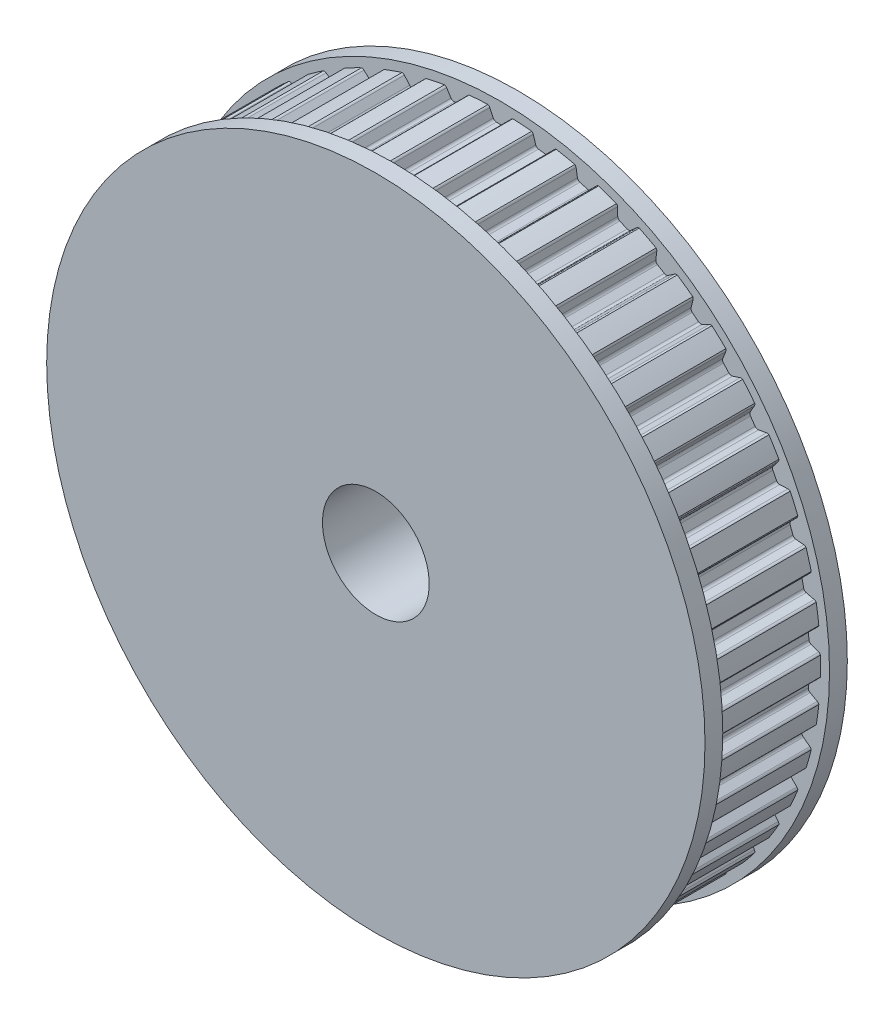
SolidWorks part; units mm, degrees
ref_plane "Front Plane" through (0, 0, 0) normal (0, 0, 1) x (1, 0, 0)
ref_plane "Top Plane" through (0, 0, 0) normal (0, 1, 0) x (1, 0, 0)
ref_plane "Right Plane" through (0, 0, 0) normal (1, 0, 0) x (0, 0, -1)
sketch "Sketch1" plane through (0, 0, 0) normal (1, 0, 0) x (0, 0, -1)
  line L0 (141.7526, 0) -> (-141.7526, 0) construction
  line L1 (0, -176.0309) -> (0, 176.0309) construction
  line L2 (15, 6) -> (-15, 6)
  line L3 (-15, 6) -> (-15, 37)
  line L4 (-15, 37) -> (-13, 37)
  line L5 (-13, 37) -> (-13, 36)
  line L6 (-13, 36) -> (-1, 36)
  line L7 (-1, 36) -> (-1, 37)
  line L8 (-1, 37) -> (1, 37)
  line L9 (15, 6) -> (15, 10)
  line L10 (15, 10) -> (1, 10)
  line L11 (1, 10) -> (1, 37)
  point P4 (0, 0)
  point P8 (0, 0)
  point P11 (0, 6)
  dimension "D1" = 30
  dimension "D2" = 6
  dimension "D3" = 31
  dimension "D4" = 2
  dimension "D5" = 30
  dimension "D6" = 12
  dimension "D7" = 10
revolve "Revolve1" add sketch "Sketch1" angle 360 about L0
sketch "Sketch2" plane through (0, 0, 1) normal (0, 0, 1) x (1, 0, 0)
  line L0 (0, -36) -> (0, 36) construction
  line L1 (0.4522, 34.73) -> (-0.4522, 34.73)
  line L2 (-0.7966, 34.9494) -> (-1.1842, 35.7807)
  line L3 (0.7966, 34.9494) -> (1.1842, 35.7807)
  line L4 (5.5481, 34.5154) -> (6.0453, 35.2861)
  line L5 (5.1771, 34.3449) -> (4.2811, 34.4681)
  line L6 (3.9698, 34.7324) -> (3.6989, 35.6086)
  line L7 (10.1963, 33.4385) -> (10.7938, 34.1343)
  line L8 (9.8055, 33.3201) -> (8.9346, 33.5641)
  line L9 (8.6622, 33.8683) -> (8.5132, 34.7733)
  line L10 (14.6545, 31.7386) -> (15.3412, 32.3466)
  line L11 (14.2512, 31.6746) -> (13.4217, 32.0349)
  line L12 (13.1932, 32.3734) -> (13.1689, 33.2902)
  line L13 (18.8398, 29.4475) -> (19.6029, 29.9564)
  line L14 (18.4315, 29.439) -> (17.6588, 29.9089)
  line L15 (17.4785, 30.2754) -> (17.5792, 31.187)
  line L16 (22.6741, 26.6079) -> (23.4994, 27.0081)
  line L17 (22.2685, 26.6551) -> (21.5669, 27.2258)
  line L18 (21.4382, 27.6134) -> (21.6621, 28.5028)
  line L19 (26.086, 23.2726) -> (26.9581, 23.5567)
  line L20 (25.6906, 23.3746) -> (25.0733, 24.0356)
  line L21 (24.9986, 24.437) -> (25.3415, 25.2877)
  line L22 (29.012, 19.5038) -> (29.9146, 19.6665)
  line L23 (28.6341, 19.6587) -> (28.1126, 20.3975)
  line L24 (28.0932, 20.8054) -> (28.5488, 21.6015)
  line L25 (31.3975, 15.3717) -> (32.3139, 15.41)
  line L26 (31.0443, 15.5766) -> (30.6282, 16.3796)
  line L27 (30.6646, 16.7863) -> (31.2243, 17.5129)
  line L28 (33.1982, 10.9532) -> (34.1113, 10.8664)
  line L29 (32.8762, 11.2043) -> (32.5733, 12.0565)
  line L30 (32.6647, 12.4544) -> (33.3181, 13.0981)
  line L31 (34.3805, 6.3307) -> (35.2732, 6.1203)
  line L32 (34.0956, 6.6233) -> (33.9116, 7.5088)
  line L33 (34.0563, 7.8906) -> (34.7913, 8.4392)
  line L34 (34.9223, 1.5903) -> (35.7781, 1.2603)
  line L35 (34.6799, 1.9189) -> (34.6182, 2.8212)
  line L36 (34.8136, 3.1798) -> (35.6164, 3.6232)
  line L37 (34.8136, -3.1798) -> (35.6164, -3.6232)
  line L38 (34.6182, -2.8212) -> (34.6799, -1.9189)
  line L39 (34.9223, -1.5903) -> (35.7781, -1.2603)
  line L40 (34.0563, -7.8906) -> (34.7913, -8.4392)
  line L41 (33.9116, -7.5088) -> (34.0956, -6.6233)
  line L42 (34.3805, -6.3307) -> (35.2732, -6.1203)
  line L43 (32.6647, -12.4544) -> (33.3181, -13.0981)
  line L44 (32.5733, -12.0565) -> (32.8762, -11.2043)
  line L45 (33.1982, -10.9532) -> (34.1113, -10.8664)
  line L46 (30.6646, -16.7863) -> (31.2243, -17.5129)
  line L47 (30.6282, -16.3796) -> (31.0443, -15.5766)
  line L48 (31.3975, -15.3717) -> (32.3139, -15.41)
  line L49 (28.0932, -20.8054) -> (28.5488, -21.6015)
  line L50 (28.1126, -20.3975) -> (28.6341, -19.6587)
  line L51 (29.012, -19.5038) -> (29.9146, -19.6665)
  line L52 (24.9986, -24.437) -> (25.3415, -25.2877)
  line L53 (25.0733, -24.0356) -> (25.6906, -23.3746)
  line L54 (26.086, -23.2726) -> (26.9581, -23.5567)
  line L55 (21.4382, -27.6134) -> (21.6621, -28.5028)
  line L56 (21.5669, -27.2258) -> (22.2685, -26.6551)
  line L57 (22.6741, -26.6079) -> (23.4994, -27.0081)
  line L58 (17.4785, -30.2754) -> (17.5792, -31.187)
  line L59 (17.6588, -29.9089) -> (18.4315, -29.439)
  line L60 (18.8398, -29.4475) -> (19.6029, -29.9564)
  line L61 (13.1932, -32.3734) -> (13.1689, -33.2902)
  line L62 (13.4217, -32.0349) -> (14.2512, -31.6746)
  line L63 (14.6545, -31.7386) -> (15.3412, -32.3466)
  line L64 (8.6622, -33.8683) -> (8.5132, -34.7733)
  line L65 (8.9346, -33.5641) -> (9.8055, -33.3201)
  line L66 (10.1963, -33.4385) -> (10.7938, -34.1343)
  line L67 (3.9698, -34.7324) -> (3.6989, -35.6086)
  line L68 (4.2811, -34.4681) -> (5.1771, -34.3449)
  line L69 (5.5481, -34.5154) -> (6.0453, -35.2861)
  line L70 (-0.7966, -34.9494) -> (-1.1842, -35.7807)
  line L71 (-0.4522, -34.73) -> (0.4522, -34.73)
  line L72 (0.7966, -34.9494) -> (1.1842, -35.7807)
  line L73 (-5.5481, -34.5154) -> (-6.0453, -35.2861)
  line L74 (-5.1771, -34.3449) -> (-4.2811, -34.4681)
  line L75 (-3.9698, -34.7324) -> (-3.6989, -35.6086)
  line L76 (-10.1963, -33.4385) -> (-10.7938, -34.1343)
  line L77 (-9.8055, -33.3201) -> (-8.9346, -33.5641)
  line L78 (-8.6622, -33.8683) -> (-8.5132, -34.7733)
  line L79 (-14.6545, -31.7386) -> (-15.3412, -32.3466)
  line L80 (-14.2512, -31.6746) -> (-13.4217, -32.0349)
  line L81 (-13.1932, -32.3734) -> (-13.1689, -33.2902)
  line L82 (-18.8398, -29.4475) -> (-19.6029, -29.9564)
  line L83 (-18.4315, -29.439) -> (-17.6588, -29.9089)
  line L84 (-17.4785, -30.2754) -> (-17.5792, -31.187)
  line L85 (-22.6741, -26.6079) -> (-23.4994, -27.0081)
  line L86 (-22.2685, -26.6551) -> (-21.5669, -27.2258)
  line L87 (-21.4382, -27.6134) -> (-21.6621, -28.5028)
  line L88 (-26.086, -23.2726) -> (-26.9581, -23.5567)
  line L89 (-25.6906, -23.3746) -> (-25.0733, -24.0356)
  line L90 (-24.9986, -24.437) -> (-25.3415, -25.2877)
  line L91 (-29.012, -19.5038) -> (-29.9146, -19.6665)
  line L92 (-28.6341, -19.6587) -> (-28.1126, -20.3975)
  line L93 (-28.0932, -20.8054) -> (-28.5488, -21.6015)
  line L94 (-31.3975, -15.3717) -> (-32.3139, -15.41)
  line L95 (-31.0443, -15.5766) -> (-30.6282, -16.3796)
  line L96 (-30.6646, -16.7863) -> (-31.2243, -17.5129)
  line L97 (-33.1982, -10.9532) -> (-34.1113, -10.8664)
  line L98 (-32.8762, -11.2043) -> (-32.5733, -12.0565)
  line L99 (-32.6647, -12.4544) -> (-33.3181, -13.0981)
  line L100 (-34.3805, -6.3307) -> (-35.2732, -6.1203)
  line L101 (-34.0956, -6.6233) -> (-33.9116, -7.5088)
  line L102 (-34.0563, -7.8906) -> (-34.7913, -8.4392)
  line L103 (-34.9223, -1.5903) -> (-35.7781, -1.2603)
  line L104 (-34.6799, -1.9189) -> (-34.6182, -2.8212)
  line L105 (-34.8136, -3.1798) -> (-35.6164, -3.6232)
  line L106 (-34.8136, 3.1798) -> (-35.6164, 3.6232)
  line L107 (-34.6182, 2.8212) -> (-34.6799, 1.9189)
  line L108 (-34.9223, 1.5903) -> (-35.7781, 1.2603)
  line L109 (-34.0563, 7.8906) -> (-34.7913, 8.4392)
  line L110 (-33.9116, 7.5088) -> (-34.0956, 6.6233)
  line L111 (-34.3805, 6.3307) -> (-35.2732, 6.1203)
  line L112 (-32.6647, 12.4544) -> (-33.3181, 13.0981)
  line L113 (-32.5733, 12.0565) -> (-32.8762, 11.2043)
  line L114 (-33.1982, 10.9532) -> (-34.1113, 10.8664)
  line L115 (-30.6646, 16.7863) -> (-31.2243, 17.5129)
  line L116 (-30.6282, 16.3796) -> (-31.0443, 15.5766)
  line L117 (-31.3975, 15.3717) -> (-32.3139, 15.41)
  line L118 (-28.0932, 20.8054) -> (-28.5488, 21.6015)
  line L119 (-28.1126, 20.3975) -> (-28.6341, 19.6587)
  line L120 (-29.012, 19.5038) -> (-29.9146, 19.6665)
  line L121 (-24.9986, 24.437) -> (-25.3415, 25.2877)
  line L122 (-25.0733, 24.0356) -> (-25.6906, 23.3746)
  line L123 (-26.086, 23.2726) -> (-26.9581, 23.5567)
  line L124 (-21.4382, 27.6134) -> (-21.6621, 28.5028)
  line L125 (-21.5669, 27.2258) -> (-22.2685, 26.6551)
  line L126 (-22.6741, 26.6079) -> (-23.4994, 27.0081)
  line L127 (-17.4785, 30.2754) -> (-17.5792, 31.187)
  line L128 (-17.6588, 29.9089) -> (-18.4315, 29.439)
  line L129 (-18.8398, 29.4475) -> (-19.6029, 29.9564)
  line L130 (-13.1932, 32.3734) -> (-13.1689, 33.2902)
  line L131 (-13.4217, 32.0349) -> (-14.2512, 31.6746)
  line L132 (-14.6545, 31.7386) -> (-15.3412, 32.3466)
  line L133 (-8.6622, 33.8683) -> (-8.5132, 34.7733)
  line L134 (-8.9346, 33.5641) -> (-9.8055, 33.3201)
  line L135 (-10.1963, 33.4385) -> (-10.7938, 34.1343)
  line L136 (-3.9698, 34.7324) -> (-3.6989, 35.6086)
  line L137 (-4.2811, 34.4681) -> (-5.1771, 34.3449)
  line L138 (-5.5481, 34.5154) -> (-6.0453, 35.2861)
  line L139 (1.5217, 36) -> (3.3945, 35.8719)
  line L140 (6.4095, 35.4575) -> (8.2474, 35.0756)
  line L141 (11.1779, 34.2545) -> (12.9467, 33.6258)
  line L142 (15.7381, 32.4134) -> (17.4049, 31.5497)
  line L143 (20.0052, 29.9685) -> (21.5388, 28.8859)
  line L144 (23.8995, 26.9653) -> (25.2715, 25.684)
  line L145 (27.3487, 23.4598) -> (28.5334, 22.0037)
  line L146 (30.2884, 19.5173) -> (31.2638, 17.9134)
  line L147 (32.6639, 15.2113) -> (33.4118, 13.4895)
  line L148 (34.431, 10.6219) -> (34.9374, 8.8143)
  line L149 (35.5566, 5.8346) -> (35.8122, 3.9748)
  line L150 (36.0199, 0.9386) -> (36.0199, -0.9386)
  line L151 (35.8122, -3.9748) -> (35.5566, -5.8346)
  line L152 (34.9374, -8.8143) -> (34.431, -10.6219)
  line L153 (33.4118, -13.4895) -> (32.6639, -15.2113)
  line L154 (31.2638, -17.9134) -> (30.2884, -19.5173)
  line L155 (28.5334, -22.0037) -> (27.3487, -23.4598)
  line L156 (25.2715, -25.684) -> (23.8995, -26.9653)
  line L157 (21.5388, -28.8859) -> (20.0052, -29.9685)
  line L158 (17.4049, -31.5497) -> (15.7381, -32.4134)
  line L159 (12.9467, -33.6258) -> (11.1779, -34.2545)
  line L160 (8.2474, -35.0756) -> (6.4095, -35.4575)
  line L161 (3.3945, -35.8719) -> (1.5217, -36)
  line L162 (-1.5217, -36) -> (-3.3945, -35.8719)
  line L163 (-6.4095, -35.4575) -> (-8.2474, -35.0756)
  line L164 (-11.1779, -34.2545) -> (-12.9467, -33.6258)
  line L165 (-15.7381, -32.4134) -> (-17.4049, -31.5497)
  line L166 (-20.0052, -29.9685) -> (-21.5388, -28.8859)
  line L167 (-23.8995, -26.9653) -> (-25.2715, -25.684)
  line L168 (-27.3487, -23.4598) -> (-28.5334, -22.0037)
  line L169 (-30.2884, -19.5173) -> (-31.2638, -17.9134)
  line L170 (-32.6639, -15.2113) -> (-33.4118, -13.4895)
  line L171 (-34.431, -10.6219) -> (-34.9374, -8.8143)
  line L172 (-35.5566, -5.8346) -> (-35.8122, -3.9748)
  line L173 (-36.0199, -0.9386) -> (-36.0199, 0.9386)
  line L174 (-35.8122, 3.9748) -> (-35.5566, 5.8346)
  line L175 (-34.9374, 8.8143) -> (-34.431, 10.6219)
  line L176 (-33.4118, 13.4895) -> (-32.6639, 15.2113)
  line L177 (-31.2638, 17.9134) -> (-30.2884, 19.5173)
  line L178 (-28.5334, 22.0037) -> (-27.3487, 23.4598)
  line L179 (-25.2715, 25.684) -> (-23.8995, 26.9653)
  line L180 (-21.5388, 28.8859) -> (-20.0052, 29.9685)
  line L181 (-17.4049, 31.5497) -> (-15.7381, 32.4134)
  line L182 (-12.9467, 33.6258) -> (-11.1779, 34.2545)
  line L183 (-8.2474, 35.0756) -> (-6.4095, 35.4575)
  line L184 (-3.3945, 35.8719) -> (-1.5217, 36)
  circle A0 centre (0, 0) radius 34.73 construction
  circle A1 centre (0, 0) radius 36 construction
  arc A2 (1.1842, 35.7807) -> (1.5217, 36) centre (1.5286, 35.6201) cw
  arc A3 (0.4522, 34.73) -> (0.7966, 34.9494) centre (0.4522, 35.11) ccw
  arc A4 (-0.4522, 34.73) -> (-0.7966, 34.9494) centre (-0.4522, 35.11) cw
  arc A5 (-1.1842, 35.7807) -> (-1.5217, 36) centre (-1.5286, 35.6201) ccw
  arc A6 (6.0453, 35.2861) -> (6.4095, 35.4575) centre (6.3646, 35.0801) cw
  arc A7 (5.1771, 34.3449) -> (5.5481, 34.5154) centre (5.2288, 34.7214) ccw
  arc A8 (4.2811, 34.4681) -> (3.9698, 34.7324) centre (4.3328, 34.8446) cw
  arc A9 (3.6989, 35.6086) -> (3.3945, 35.8719) centre (3.3359, 35.4964) ccw
  arc A10 (10.7938, 34.1343) -> (11.1779, 34.2545) centre (11.0821, 33.8868) cw
  arc A11 (9.8055, 33.3201) -> (10.1963, 33.4385) centre (9.908, 33.686) ccw
  arc A12 (8.9346, 33.5641) -> (8.6622, 33.8683) centre (9.0371, 33.93) cw
  arc A13 (8.5132, 34.7733) -> (8.2474, 35.0756) centre (8.1382, 34.7116) ccw
  arc A14 (15.3412, 32.3466) -> (15.7381, 32.4134) centre (15.5931, 32.0621) cw
  arc A15 (14.2512, 31.6746) -> (14.6545, 31.7386) centre (14.4026, 32.0231) ccw
  arc A16 (13.4217, 32.0349) -> (13.1932, 32.3734) centre (13.5731, 32.3834) cw
  arc A17 (13.1689, 33.2902) -> (12.9467, 33.6258) centre (12.789, 33.2801) ccw
  arc A18 (19.6029, 29.9564) -> (20.0052, 29.9685) centre (19.8137, 29.6402) cw
  arc A19 (18.4315, 29.439) -> (18.8398, 29.4475) centre (18.629, 29.7637) ccw
  arc A20 (17.6588, 29.9089) -> (17.4785, 30.2754) centre (17.8562, 30.2336) cw
  arc A21 (17.5792, 31.187) -> (17.4049, 31.5497) centre (17.2015, 31.2287) ccw
  arc A22 (23.4994, 27.0081) -> (23.8995, 26.9653) centre (23.6652, 26.6662) cw
  arc A23 (22.2685, 26.6551) -> (22.6741, 26.6079) centre (22.5083, 26.9498) ccw
  arc A24 (21.5669, 27.2258) -> (21.4382, 27.6134) centre (21.8067, 27.5206) cw
  arc A25 (21.6621, 28.5028) -> (21.5388, 28.8859) centre (21.2936, 28.5956) ccw
  arc A26 (26.9581, 23.5567) -> (27.3487, 23.4598) centre (27.0758, 23.1954) cw
  arc A27 (25.6906, 23.3746) -> (26.086, 23.2726) centre (25.9683, 23.634) ccw
  arc A28 (25.0733, 24.0356) -> (24.9986, 24.437) centre (25.351, 24.2949) cw
  arc A29 (25.3415, 25.2877) -> (25.2715, 25.684) centre (24.9891, 25.4298) ccw
  arc A30 (29.9146, 19.6665) -> (30.2884, 19.5173) centre (29.982, 19.2926) cw
  arc A31 (28.6341, 19.6587) -> (29.012, 19.5038) centre (28.9446, 19.8778) ccw
  arc A32 (28.1126, 20.3975) -> (28.0932, 20.8054) centre (28.423, 20.6167) cw
  arc A33 (28.5488, 21.6015) -> (28.5334, 22.0037) centre (28.219, 21.7902) ccw
  arc A34 (32.3139, 15.41) -> (32.6639, 15.2113) centre (32.3298, 15.0303) cw
  arc A35 (31.0443, 15.5766) -> (31.3975, 15.3717) centre (31.3817, 15.7514) ccw
  arc A36 (30.6282, 16.3796) -> (30.6646, 16.7863) centre (30.9656, 16.5544) cw
  arc A37 (31.2243, 17.5129) -> (31.2638, 17.9134) centre (30.9233, 17.7448) ccw
  arc A38 (34.1113, 10.8664) -> (34.431, 10.6219) centre (34.0753, 10.4881) cw
  arc A39 (32.8762, 11.2043) -> (33.1982, 10.9532) centre (33.2342, 11.3315) ccw
  arc A40 (32.5733, 12.0565) -> (32.6647, 12.4544) centre (32.9313, 12.1837) cw
  arc A41 (33.3181, 13.0981) -> (33.4118, 13.4895) centre (33.0515, 13.3688) ccw
  arc A42 (35.2732, 6.1203) -> (35.5566, 5.8346) centre (35.186, 5.7505) cw
  arc A43 (34.0956, 6.6233) -> (34.3805, 6.3307) centre (34.4676, 6.7006) ccw
  arc A44 (33.9116, 7.5088) -> (34.0563, 7.8906) centre (34.2836, 7.5861) cw
  arc A45 (34.7913, 8.4392) -> (34.9374, 8.8143) centre (34.564, 8.7438) ccw
  arc A46 (35.7781, 1.2603) -> (36.0199, 0.9386) centre (35.6413, 0.9057) cw
  arc A47 (34.6799, 1.9189) -> (34.9223, 1.5903) centre (35.059, 1.9448) ccw
  arc A48 (34.6182, 2.8212) -> (34.8136, 3.1798) centre (34.9973, 2.8471) cw
  arc A49 (35.6164, 3.6232) -> (35.8122, 3.9748) centre (35.4327, 3.9559) ccw
  arc A50 (35.6164, -3.6232) -> (35.8122, -3.9748) centre (35.4327, -3.9559) cw
  arc A51 (34.6182, -2.8212) -> (34.8136, -3.1798) centre (34.9973, -2.8471) ccw
  arc A52 (34.6799, -1.9189) -> (34.9223, -1.5903) centre (35.059, -1.9448) cw
  arc A53 (35.7781, -1.2603) -> (36.0199, -0.9386) centre (35.6413, -0.9057) ccw
  arc A54 (34.7913, -8.4392) -> (34.9374, -8.8143) centre (34.564, -8.7438) cw
  arc A55 (33.9116, -7.5088) -> (34.0563, -7.8906) centre (34.2836, -7.5861) ccw
  arc A56 (34.0956, -6.6233) -> (34.3805, -6.3307) centre (34.4676, -6.7006) cw
  arc A57 (35.2732, -6.1203) -> (35.5566, -5.8346) centre (35.186, -5.7505) ccw
  arc A58 (33.3181, -13.0981) -> (33.4118, -13.4895) centre (33.0515, -13.3688) cw
  arc A59 (32.5733, -12.0565) -> (32.6647, -12.4544) centre (32.9313, -12.1837) ccw
  arc A60 (32.8762, -11.2043) -> (33.1982, -10.9532) centre (33.2342, -11.3315) cw
  arc A61 (34.1113, -10.8664) -> (34.431, -10.6219) centre (34.0753, -10.4881) ccw
  arc A62 (31.2243, -17.5129) -> (31.2638, -17.9134) centre (30.9233, -17.7448) cw
  arc A63 (30.6282, -16.3796) -> (30.6646, -16.7863) centre (30.9656, -16.5544) ccw
  arc A64 (31.0443, -15.5766) -> (31.3975, -15.3717) centre (31.3817, -15.7514) cw
  arc A65 (32.3139, -15.41) -> (32.6639, -15.2113) centre (32.3298, -15.0303) ccw
  arc A66 (28.5488, -21.6015) -> (28.5334, -22.0037) centre (28.219, -21.7902) cw
  arc A67 (28.1126, -20.3975) -> (28.0932, -20.8054) centre (28.423, -20.6167) ccw
  arc A68 (28.6341, -19.6587) -> (29.012, -19.5038) centre (28.9446, -19.8778) cw
  arc A69 (29.9146, -19.6665) -> (30.2884, -19.5173) centre (29.982, -19.2926) ccw
  arc A70 (25.3415, -25.2877) -> (25.2715, -25.684) centre (24.9891, -25.4298) cw
  arc A71 (25.0733, -24.0356) -> (24.9986, -24.437) centre (25.351, -24.2949) ccw
  arc A72 (25.6906, -23.3746) -> (26.086, -23.2726) centre (25.9683, -23.634) cw
  arc A73 (26.9581, -23.5567) -> (27.3487, -23.4598) centre (27.0758, -23.1954) ccw
  arc A74 (21.6621, -28.5028) -> (21.5388, -28.8859) centre (21.2936, -28.5956) cw
  arc A75 (21.5669, -27.2258) -> (21.4382, -27.6134) centre (21.8067, -27.5206) ccw
  arc A76 (22.2685, -26.6551) -> (22.6741, -26.6079) centre (22.5083, -26.9498) cw
  arc A77 (23.4994, -27.0081) -> (23.8995, -26.9653) centre (23.6652, -26.6662) ccw
  arc A78 (17.5792, -31.187) -> (17.4049, -31.5497) centre (17.2015, -31.2287) cw
  arc A79 (17.6588, -29.9089) -> (17.4785, -30.2754) centre (17.8562, -30.2336) ccw
  arc A80 (18.4315, -29.439) -> (18.8398, -29.4475) centre (18.629, -29.7637) cw
  arc A81 (19.6029, -29.9564) -> (20.0052, -29.9685) centre (19.8137, -29.6402) ccw
  arc A82 (13.1689, -33.2902) -> (12.9467, -33.6258) centre (12.789, -33.2801) cw
  arc A83 (13.4217, -32.0349) -> (13.1932, -32.3734) centre (13.5731, -32.3834) ccw
  arc A84 (14.2512, -31.6746) -> (14.6545, -31.7386) centre (14.4026, -32.0231) cw
  arc A85 (15.3412, -32.3466) -> (15.7381, -32.4134) centre (15.5931, -32.0621) ccw
  arc A86 (8.5132, -34.7733) -> (8.2474, -35.0756) centre (8.1382, -34.7116) cw
  arc A87 (8.9346, -33.5641) -> (8.6622, -33.8683) centre (9.0371, -33.93) ccw
  arc A88 (9.8055, -33.3201) -> (10.1963, -33.4385) centre (9.908, -33.686) cw
  arc A89 (10.7938, -34.1343) -> (11.1779, -34.2545) centre (11.0821, -33.8868) ccw
  arc A90 (3.6989, -35.6086) -> (3.3945, -35.8719) centre (3.3359, -35.4964) cw
  arc A91 (4.2811, -34.4681) -> (3.9698, -34.7324) centre (4.3328, -34.8446) ccw
  arc A92 (5.1771, -34.3449) -> (5.5481, -34.5154) centre (5.2288, -34.7214) cw
  arc A93 (6.0453, -35.2861) -> (6.4095, -35.4575) centre (6.3646, -35.0801) ccw
  arc A94 (-1.1842, -35.7807) -> (-1.5217, -36) centre (-1.5286, -35.6201) cw
  arc A95 (-0.4522, -34.73) -> (-0.7966, -34.9494) centre (-0.4522, -35.11) ccw
  arc A96 (0.4522, -34.73) -> (0.7966, -34.9494) centre (0.4522, -35.11) cw
  arc A97 (1.1842, -35.7807) -> (1.5217, -36) centre (1.5286, -35.6201) ccw
  arc A98 (-6.0453, -35.2861) -> (-6.4095, -35.4575) centre (-6.3646, -35.0801) cw
  arc A99 (-5.1771, -34.3449) -> (-5.5481, -34.5154) centre (-5.2288, -34.7214) ccw
  arc A100 (-4.2811, -34.4681) -> (-3.9698, -34.7324) centre (-4.3328, -34.8446) cw
  arc A101 (-3.6989, -35.6086) -> (-3.3945, -35.8719) centre (-3.3359, -35.4964) ccw
  arc A102 (-10.7938, -34.1343) -> (-11.1779, -34.2545) centre (-11.0821, -33.8868) cw
  arc A103 (-9.8055, -33.3201) -> (-10.1963, -33.4385) centre (-9.908, -33.686) ccw
  arc A104 (-8.9346, -33.5641) -> (-8.6622, -33.8683) centre (-9.0371, -33.93) cw
  arc A105 (-8.5132, -34.7733) -> (-8.2474, -35.0756) centre (-8.1382, -34.7116) ccw
  arc A106 (-15.3412, -32.3466) -> (-15.7381, -32.4134) centre (-15.5931, -32.0621) cw
  arc A107 (-14.2512, -31.6746) -> (-14.6545, -31.7386) centre (-14.4026, -32.0231) ccw
  arc A108 (-13.4217, -32.0349) -> (-13.1932, -32.3734) centre (-13.5731, -32.3834) cw
  arc A109 (-13.1689, -33.2902) -> (-12.9467, -33.6258) centre (-12.789, -33.2801) ccw
  arc A110 (-19.6029, -29.9564) -> (-20.0052, -29.9685) centre (-19.8137, -29.6402) cw
  arc A111 (-18.4315, -29.439) -> (-18.8398, -29.4475) centre (-18.629, -29.7637) ccw
  arc A112 (-17.6588, -29.9089) -> (-17.4785, -30.2754) centre (-17.8562, -30.2336) cw
  arc A113 (-17.5792, -31.187) -> (-17.4049, -31.5497) centre (-17.2015, -31.2287) ccw
  arc A114 (-23.4994, -27.0081) -> (-23.8995, -26.9653) centre (-23.6652, -26.6662) cw
  arc A115 (-22.2685, -26.6551) -> (-22.6741, -26.6079) centre (-22.5083, -26.9498) ccw
  arc A116 (-21.5669, -27.2258) -> (-21.4382, -27.6134) centre (-21.8067, -27.5206) cw
  arc A117 (-21.6621, -28.5028) -> (-21.5388, -28.8859) centre (-21.2936, -28.5956) ccw
  arc A118 (-26.9581, -23.5567) -> (-27.3487, -23.4598) centre (-27.0758, -23.1954) cw
  arc A119 (-25.6906, -23.3746) -> (-26.086, -23.2726) centre (-25.9683, -23.634) ccw
  arc A120 (-25.0733, -24.0356) -> (-24.9986, -24.437) centre (-25.351, -24.2949) cw
  arc A121 (-25.3415, -25.2877) -> (-25.2715, -25.684) centre (-24.9891, -25.4298) ccw
  arc A122 (-29.9146, -19.6665) -> (-30.2884, -19.5173) centre (-29.982, -19.2926) cw
  arc A123 (-28.6341, -19.6587) -> (-29.012, -19.5038) centre (-28.9446, -19.8778) ccw
  arc A124 (-28.1126, -20.3975) -> (-28.0932, -20.8054) centre (-28.423, -20.6167) cw
  arc A125 (-28.5488, -21.6015) -> (-28.5334, -22.0037) centre (-28.219, -21.7902) ccw
  arc A126 (-32.3139, -15.41) -> (-32.6639, -15.2113) centre (-32.3298, -15.0303) cw
  arc A127 (-31.0443, -15.5766) -> (-31.3975, -15.3717) centre (-31.3817, -15.7514) ccw
  arc A128 (-30.6282, -16.3796) -> (-30.6646, -16.7863) centre (-30.9656, -16.5544) cw
  arc A129 (-31.2243, -17.5129) -> (-31.2638, -17.9134) centre (-30.9233, -17.7448) ccw
  arc A130 (-34.1113, -10.8664) -> (-34.431, -10.6219) centre (-34.0753, -10.4881) cw
  arc A131 (-32.8762, -11.2043) -> (-33.1982, -10.9532) centre (-33.2342, -11.3315) ccw
  arc A132 (-32.5733, -12.0565) -> (-32.6647, -12.4544) centre (-32.9313, -12.1837) cw
  arc A133 (-33.3181, -13.0981) -> (-33.4118, -13.4895) centre (-33.0515, -13.3688) ccw
  arc A134 (-35.2732, -6.1203) -> (-35.5566, -5.8346) centre (-35.186, -5.7505) cw
  arc A135 (-34.0956, -6.6233) -> (-34.3805, -6.3307) centre (-34.4676, -6.7006) ccw
  arc A136 (-33.9116, -7.5088) -> (-34.0563, -7.8906) centre (-34.2836, -7.5861) cw
  arc A137 (-34.7913, -8.4392) -> (-34.9374, -8.8143) centre (-34.564, -8.7438) ccw
  arc A138 (-35.7781, -1.2603) -> (-36.0199, -0.9386) centre (-35.6413, -0.9057) cw
  arc A139 (-34.6799, -1.9189) -> (-34.9223, -1.5903) centre (-35.059, -1.9448) ccw
  arc A140 (-34.6182, -2.8212) -> (-34.8136, -3.1798) centre (-34.9973, -2.8471) cw
  arc A141 (-35.6164, -3.6232) -> (-35.8122, -3.9748) centre (-35.4327, -3.9559) ccw
  arc A142 (-35.6164, 3.6232) -> (-35.8122, 3.9748) centre (-35.4327, 3.9559) cw
  arc A143 (-34.6182, 2.8212) -> (-34.8136, 3.1798) centre (-34.9973, 2.8471) ccw
  arc A144 (-34.6799, 1.9189) -> (-34.9223, 1.5903) centre (-35.059, 1.9448) cw
  arc A145 (-35.7781, 1.2603) -> (-36.0199, 0.9386) centre (-35.6413, 0.9057) ccw
  arc A146 (-34.7913, 8.4392) -> (-34.9374, 8.8143) centre (-34.564, 8.7438) cw
  arc A147 (-33.9116, 7.5088) -> (-34.0563, 7.8906) centre (-34.2836, 7.5861) ccw
  arc A148 (-34.0956, 6.6233) -> (-34.3805, 6.3307) centre (-34.4676, 6.7006) cw
  arc A149 (-35.2732, 6.1203) -> (-35.5566, 5.8346) centre (-35.186, 5.7505) ccw
  arc A150 (-33.3181, 13.0981) -> (-33.4118, 13.4895) centre (-33.0515, 13.3688) cw
  arc A151 (-32.5733, 12.0565) -> (-32.6647, 12.4544) centre (-32.9313, 12.1837) ccw
  arc A152 (-32.8762, 11.2043) -> (-33.1982, 10.9532) centre (-33.2342, 11.3315) cw
  arc A153 (-34.1113, 10.8664) -> (-34.431, 10.6219) centre (-34.0753, 10.4881) ccw
  arc A154 (-31.2243, 17.5129) -> (-31.2638, 17.9134) centre (-30.9233, 17.7448) cw
  arc A155 (-30.6282, 16.3796) -> (-30.6646, 16.7863) centre (-30.9656, 16.5544) ccw
  arc A156 (-31.0443, 15.5766) -> (-31.3975, 15.3717) centre (-31.3817, 15.7514) cw
  arc A157 (-32.3139, 15.41) -> (-32.6639, 15.2113) centre (-32.3298, 15.0303) ccw
  arc A158 (-28.5488, 21.6015) -> (-28.5334, 22.0037) centre (-28.219, 21.7902) cw
  arc A159 (-28.1126, 20.3975) -> (-28.0932, 20.8054) centre (-28.423, 20.6167) ccw
  arc A160 (-28.6341, 19.6587) -> (-29.012, 19.5038) centre (-28.9446, 19.8778) cw
  arc A161 (-29.9146, 19.6665) -> (-30.2884, 19.5173) centre (-29.982, 19.2926) ccw
  arc A162 (-25.3415, 25.2877) -> (-25.2715, 25.684) centre (-24.9891, 25.4298) cw
  arc A163 (-25.0733, 24.0356) -> (-24.9986, 24.437) centre (-25.351, 24.2949) ccw
  arc A164 (-25.6906, 23.3746) -> (-26.086, 23.2726) centre (-25.9683, 23.634) cw
  arc A165 (-26.9581, 23.5567) -> (-27.3487, 23.4598) centre (-27.0758, 23.1954) ccw
  arc A166 (-21.6621, 28.5028) -> (-21.5388, 28.8859) centre (-21.2936, 28.5956) cw
  arc A167 (-21.5669, 27.2258) -> (-21.4382, 27.6134) centre (-21.8067, 27.5206) ccw
  arc A168 (-22.2685, 26.6551) -> (-22.6741, 26.6079) centre (-22.5083, 26.9498) cw
  arc A169 (-23.4994, 27.0081) -> (-23.8995, 26.9653) centre (-23.6652, 26.6662) ccw
  arc A170 (-17.5792, 31.187) -> (-17.4049, 31.5497) centre (-17.2015, 31.2287) cw
  arc A171 (-17.6588, 29.9089) -> (-17.4785, 30.2754) centre (-17.8562, 30.2336) ccw
  arc A172 (-18.4315, 29.439) -> (-18.8398, 29.4475) centre (-18.629, 29.7637) cw
  arc A173 (-19.6029, 29.9564) -> (-20.0052, 29.9685) centre (-19.8137, 29.6402) ccw
  arc A174 (-13.1689, 33.2902) -> (-12.9467, 33.6258) centre (-12.789, 33.2801) cw
  arc A175 (-13.4217, 32.0349) -> (-13.1932, 32.3734) centre (-13.5731, 32.3834) ccw
  arc A176 (-14.2512, 31.6746) -> (-14.6545, 31.7386) centre (-14.4026, 32.0231) cw
  arc A177 (-15.3412, 32.3466) -> (-15.7381, 32.4134) centre (-15.5931, 32.0621) ccw
  arc A178 (-8.5132, 34.7733) -> (-8.2474, 35.0756) centre (-8.1382, 34.7116) cw
  arc A179 (-8.9346, 33.5641) -> (-8.6622, 33.8683) centre (-9.0371, 33.93) ccw
  arc A180 (-9.8055, 33.3201) -> (-10.1963, 33.4385) centre (-9.908, 33.686) cw
  arc A181 (-10.7938, 34.1343) -> (-11.1779, 34.2545) centre (-11.0821, 33.8868) ccw
  arc A182 (-3.6989, 35.6086) -> (-3.3945, 35.8719) centre (-3.3359, 35.4964) cw
  arc A183 (-4.2811, 34.4681) -> (-3.9698, 34.7324) centre (-4.3328, 34.8446) ccw
  arc A184 (-5.1771, 34.3449) -> (-5.5481, 34.5154) centre (-5.2288, 34.7214) cw
  arc A185 (-6.0453, 35.2861) -> (-6.4095, 35.4575) centre (-6.3646, 35.0801) ccw
  point P7 (2.4581, 35.9359)
  point P10 (0, 34.73)
  point P19 (0.6943, 34.73)
  point P22 (-0.6943, 34.73)
  point P564 (0, 0)
  point P655 (0, 0)
  dimension "D1" = 69.46
  dimension "D3" = 1.5932
  dimension "D6" = 50
  dimension "D4" = 72
  dimension "D7" = 0.38
  dimension "D10" = 1.8772
  dimension "D2" = 1.2059
  dimension "D5" = 1.27
  dimension "D8" = 46
  dimension "D9" = 0.7251
extrude "Cut-Extrude1" cut sketch "Sketch2" along normal up to surface (12 mm away) flip side to cut up to face at (-36, 0, 13)
